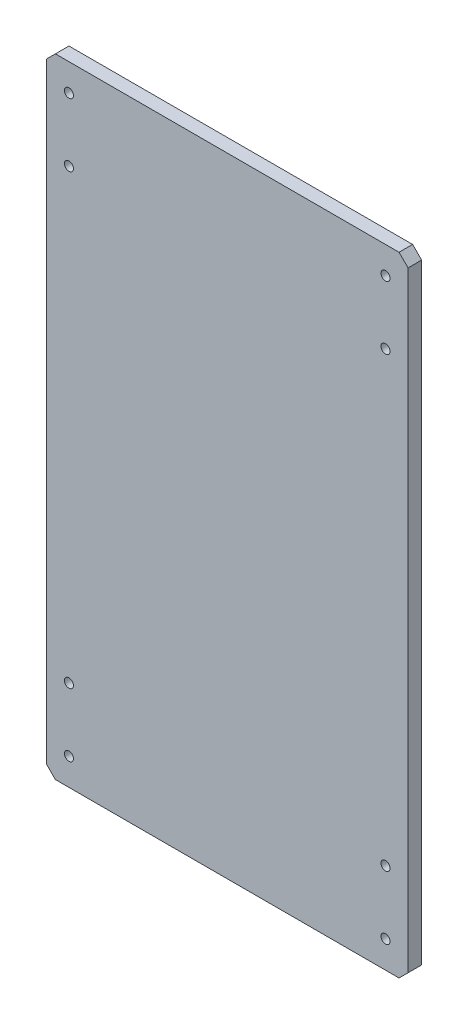
SolidWorks part; units mm, degrees
ref_plane "Front Plane" through (0, 0, 0) normal (0, 0, 1) x (1, 0, 0)
ref_plane "Top Plane" through (0, 0, 0) normal (0, 1, 0) x (1, 0, 0)
ref_plane "Right Plane" through (0, 0, 0) normal (1, 0, 0) x (0, 0, -1)
ref_plane "Plane1" through (0, 0, 3) normal (0, 0, 1) x (1, 0, 0)
sketch "Sketch1" plane through (0, 0, 3) normal (0, 0, 1) x (1, 0, 0)
  line L0 (-38, -69.5) -> (38, -69.5)
  line L1 (38, -69.5) -> (40, -67.5)
  line L2 (40, -67.5) -> (40, 67.5)
  line L3 (40, 67.5) -> (38, 69.5)
  line L4 (38, 69.5) -> (-38, 69.5)
  line L5 (-38, 69.5) -> (-40, 67.5)
  line L6 (-40, 67.5) -> (-40, -67.5)
  line L7 (-40, -67.5) -> (-38, -69.5)
  circle A0 centre (35, 49.5) radius 1
  circle A1 centre (-35, -63.5) radius 1
  circle A2 centre (35, 63.5) radius 1
  circle A3 centre (-35, -49.5) radius 1
  circle A4 centre (-35, 49.5) radius 1
  circle A5 centre (-35, 63.5) radius 1
  circle A6 centre (35, -49.5) radius 1
  circle A7 centre (35, -63.5) radius 1
extrude "Boss-Extrude1" add sketch "Sketch1" against normal blind 3
sketch "Sketch2" plane through (0, 0, 0) normal (0, 0, -1) x (-1, 0, 0)
  line L0 (0, 46.2723) -> (0, 38.6867) construction
  line L1 (1.7068, 46.2723) -> (1.7068, 38.6867)
  line L2 (-1.7068, 46.2723) -> (-1.7068, 38.6867)
  line L3 (-35.2731, 42.4795) -> (35.4628, 42.4795) construction
  line L4 (35.4628, 42.4795) -> (35.4628, -44.9448) construction
  line L5 (35.4628, -44.9448) -> (-35.2731, -44.9448) construction
  line L6 (-35.2731, -44.9448) -> (-35.2731, 42.4795) construction
  line L7 (0, 3.7928) -> (0, -3.7928) construction
  line L8 (1.7068, 3.7928) -> (1.7068, -3.7928)
  line L9 (-1.7068, 3.7928) -> (-1.7068, -3.7928)
  line L10 (-35.2731, 46.2723) -> (-35.2731, 38.6867) construction
  line L11 (-33.5664, 46.2723) -> (-33.5664, 38.6867)
  line L12 (-36.9799, 46.2723) -> (-36.9799, 38.6867)
  line L13 (0, 3.7928) -> (0, -3.7928) construction
  line L14 (1.7068, 3.7928) -> (1.7068, -3.7928)
  line L15 (-1.7068, 3.7928) -> (-1.7068, -3.7928)
  line L16 (35.4628, 46.2723) -> (35.4628, 38.6867) construction
  line L17 (37.1695, 46.2723) -> (37.1695, 38.6867)
  line L18 (33.756, 46.2723) -> (33.756, 38.6867)
  line L19 (0, -41.152) -> (0, -48.7376) construction
  line L20 (1.7068, -41.152) -> (1.7068, -48.7376)
  line L21 (-1.7068, -41.152) -> (-1.7068, -48.7376)
  line L22 (-35.2731, -41.152) -> (-35.2731, -48.7376) construction
  line L23 (-33.5664, -41.152) -> (-33.5664, -48.7376)
  line L24 (-36.9799, -41.152) -> (-36.9799, -48.7376)
  line L25 (0, -41.152) -> (0, -48.7376) construction
  line L26 (1.7068, -41.152) -> (1.7068, -48.7376)
  line L27 (-1.7068, -41.152) -> (-1.7068, -48.7376)
  line L28 (-35.2731, 3.7928) -> (-35.2731, -3.7928) construction
  line L29 (-33.5664, 3.7928) -> (-33.5664, -3.7928)
  line L30 (-36.9799, 3.7928) -> (-36.9799, -3.7928)
  line L31 (35.4628, -41.152) -> (35.4628, -48.7376) construction
  line L32 (37.1695, -41.152) -> (37.1695, -48.7376)
  line L33 (33.756, -41.152) -> (33.756, -48.7376)
  line L34 (35.4628, 3.7928) -> (35.4628, -3.7928) construction
  line L35 (37.1695, 3.7928) -> (37.1695, -3.7928)
  line L36 (33.756, 3.7928) -> (33.756, -3.7928)
  arc A0 (1.7068, 46.2723) -> (-1.7068, 46.2723) centre (0, 46.2723) ccw
  arc A1 (-1.7068, 38.6867) -> (1.7068, 38.6867) centre (0, 38.6867) ccw
  arc A2 (1.7068, 3.7928) -> (-1.7068, 3.7928) centre (0, 3.7928) ccw
  arc A3 (-1.7068, -3.7928) -> (1.7068, -3.7928) centre (0, -3.7928) ccw
  arc A4 (-33.5664, 46.2723) -> (-36.9799, 46.2723) centre (-35.2731, 46.2723) ccw
  arc A5 (-36.9799, 38.6867) -> (-33.5664, 38.6867) centre (-35.2731, 38.6867) ccw
  arc A6 (1.7068, 3.7928) -> (-1.7068, 3.7928) centre (0, 3.7928) ccw
  arc A7 (-1.7068, -3.7928) -> (1.7068, -3.7928) centre (0, -3.7928) ccw
  arc A8 (37.1695, 46.2723) -> (33.756, 46.2723) centre (35.4628, 46.2723) ccw
  arc A9 (33.756, 38.6867) -> (37.1695, 38.6867) centre (35.4628, 38.6867) ccw
  arc A10 (1.7068, -41.152) -> (-1.7068, -41.152) centre (0, -41.152) ccw
  arc A11 (-1.7068, -48.7376) -> (1.7068, -48.7376) centre (0, -48.7376) ccw
  arc A12 (-33.5664, -41.152) -> (-36.9799, -41.152) centre (-35.2731, -41.152) ccw
  arc A13 (-36.9799, -48.7376) -> (-33.5664, -48.7376) centre (-35.2731, -48.7376) ccw
  arc A14 (1.7068, -41.152) -> (-1.7068, -41.152) centre (0, -41.152) ccw
  arc A15 (-1.7068, -48.7376) -> (1.7068, -48.7376) centre (0, -48.7376) ccw
  arc A16 (-33.5664, 3.7928) -> (-36.9799, 3.7928) centre (-35.2731, 3.7928) ccw
  arc A17 (-36.9799, -3.7928) -> (-33.5664, -3.7928) centre (-35.2731, -3.7928) ccw
  arc A18 (37.1695, -41.152) -> (33.756, -41.152) centre (35.4628, -41.152) ccw
  arc A19 (33.756, -48.7376) -> (37.1695, -48.7376) centre (35.4628, -48.7376) ccw
  arc A20 (37.1695, 3.7928) -> (33.756, 3.7928) centre (35.4628, 3.7928) ccw
  arc A21 (33.756, -3.7928) -> (37.1695, -3.7928) centre (35.4628, -3.7928) ccw
  point P2 (0, 42.4795)
  point P13 (0, 0)
  point P20 (-35.2731, 42.4795)
  point P27 (0, 0)
  point P34 (35.4628, 42.4795)
  point P41 (0, -44.9448)
  point P48 (-35.2731, -44.9448)
  point P55 (0, -44.9448)
  point P62 (-35.2731, 0)
  point P69 (35.4628, -44.9448)
  point P76 (35.4628, 0)
  point P81 (0, 0)
  point P82 (0, 0)
  dimension "D4" = 1.7068
  dimension "D1" = 70.7359
  dimension "D2" = 87.4243
  dimension "D3" = 7.5856
extrude "Cut-Extrude4" cut sketch "Sketch2" against normal blind 1.5 contours L2 A1 L1 A0 | L35 A21 L36 A20 | A18 L33 A19 L32 | A10 L21 A11 L20 | A3 L8 A2 L9 | A9 L17 A8 L18 | A5 L11 A4 L12 | A16 L30 A17 L29 | A12 L24 A13 L23
